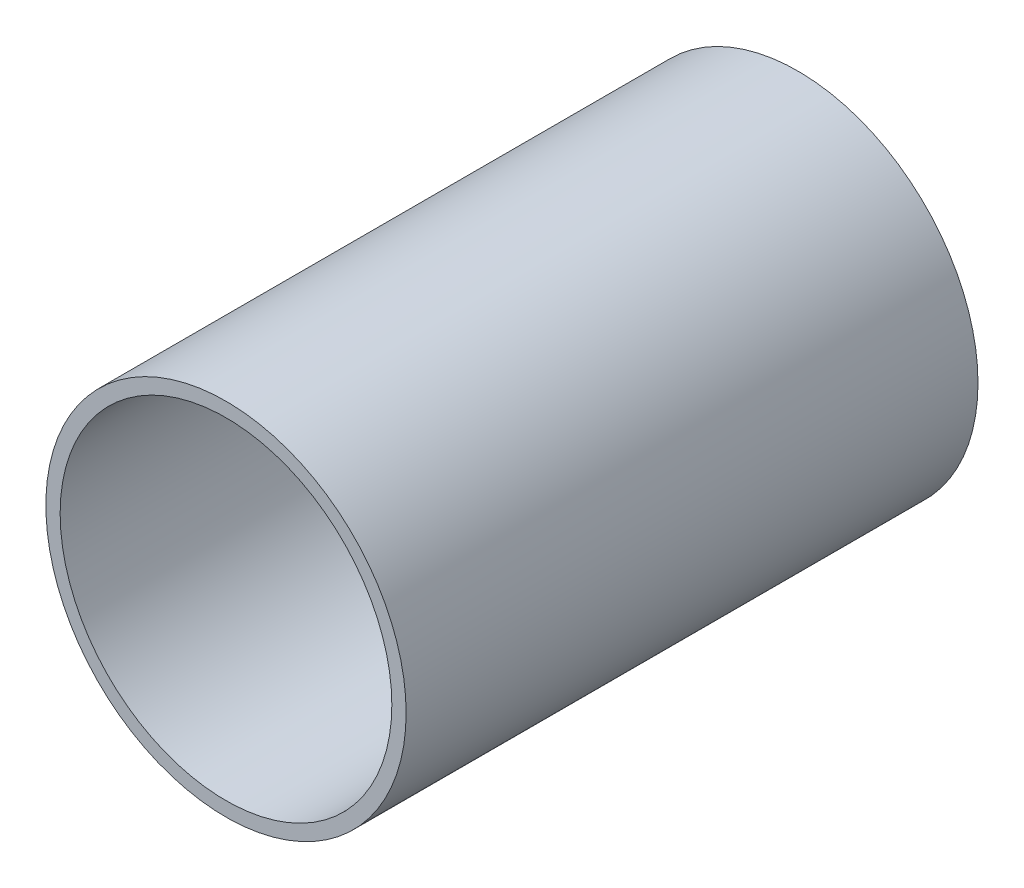
SolidWorks part; units mm, degrees
ref_plane "Front" through (0, 0, 0) normal (0, 0, 1) x (1, 0, 0)
ref_plane "Top" through (0, 0, 0) normal (0, 1, 0) x (1, 0, 0)
ref_plane "Right" through (0, 0, 0) normal (1, 0, 0) x (0, 0, -1)
sketch "Esquisse1" plane through (0, 0, 0) normal (0, 0, 1) x (1, 0, 0)
  circle A0 centre (0, 0) radius 31.5
  circle A1 centre (0, 0) radius 29
  dimension "D1" = 63
  dimension "D2" = 58
extrude "Boss.-Extru.1" add sketch "Esquisse1" along normal blind 100
